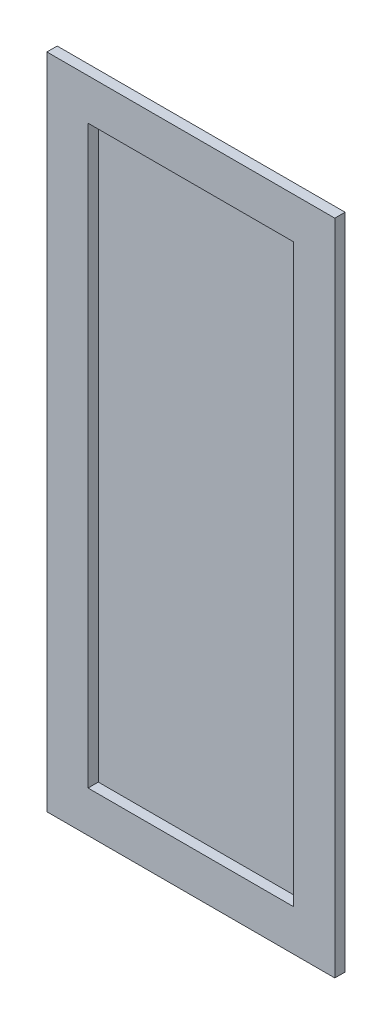
SolidWorks part; units mm, degrees
ref_plane "前视基准面" through (0, 0, 0) normal (0, 0, 1) x (1, 0, 0)
ref_plane "上视基准面" through (0, 0, 0) normal (0, 1, 0) x (1, 0, 0)
ref_plane "右视基准面" through (0, 0, 0) normal (1, 0, 0) x (0, 0, -1)
other "Configuration Table"
sketch "草图1" plane through (0, 0, 0) normal (0, 0, 1) x (1, 0, 0)
  line L1 (-60, -150) -> (60, -150)
  line L2 (-60, -150) -> (-60, 150)
  line L3 (-60, 150) -> (60, 150)
  line L4 (60, -150) -> (60, 150)
  line L5 (0, 150) -> (0, -150) construction
  line L6 (-60, 0) -> (60, 0) construction
  point P0 (0, 0)
  dimension "D1" = 120
  dimension "D2" = 300
extrude "凸台-拉伸1" add sketch "草图1" along normal blind 5
sketch "草图2" plane through (0, 0, 5) normal (0, 0, 1) x (1, 0, 0)
  line L8 (70, -160) -> (70, 160)
  line L9 (70, 160) -> (-70, 160)
  line L10 (-70, 160) -> (-70, -160)
  line L11 (-70, -160) -> (70, -160)
  line L12 (70, -160) -> (70, 160)
  line L13 (70, 160) -> (-70, 160)
  line L14 (-70, 160) -> (-70, -160)
  line L15 (-70, -160) -> (70, -160)
  line L16 (50, -140) -> (50, 140)
  line L17 (50, 140) -> (-50, 140)
  line L18 (-50, 140) -> (-50, -140)
  line L19 (-50, -140) -> (50, -140)
  line L20 (50, -140) -> (50, 140)
  line L21 (50, 140) -> (-50, 140)
  line L22 (-50, 140) -> (-50, -140)
  line L23 (-50, -140) -> (50, -140)
  dimension "D1" = 10
  dimension "D2" = 10
extrude "凸台-拉伸2" add sketch "草图2" along normal blind 5
